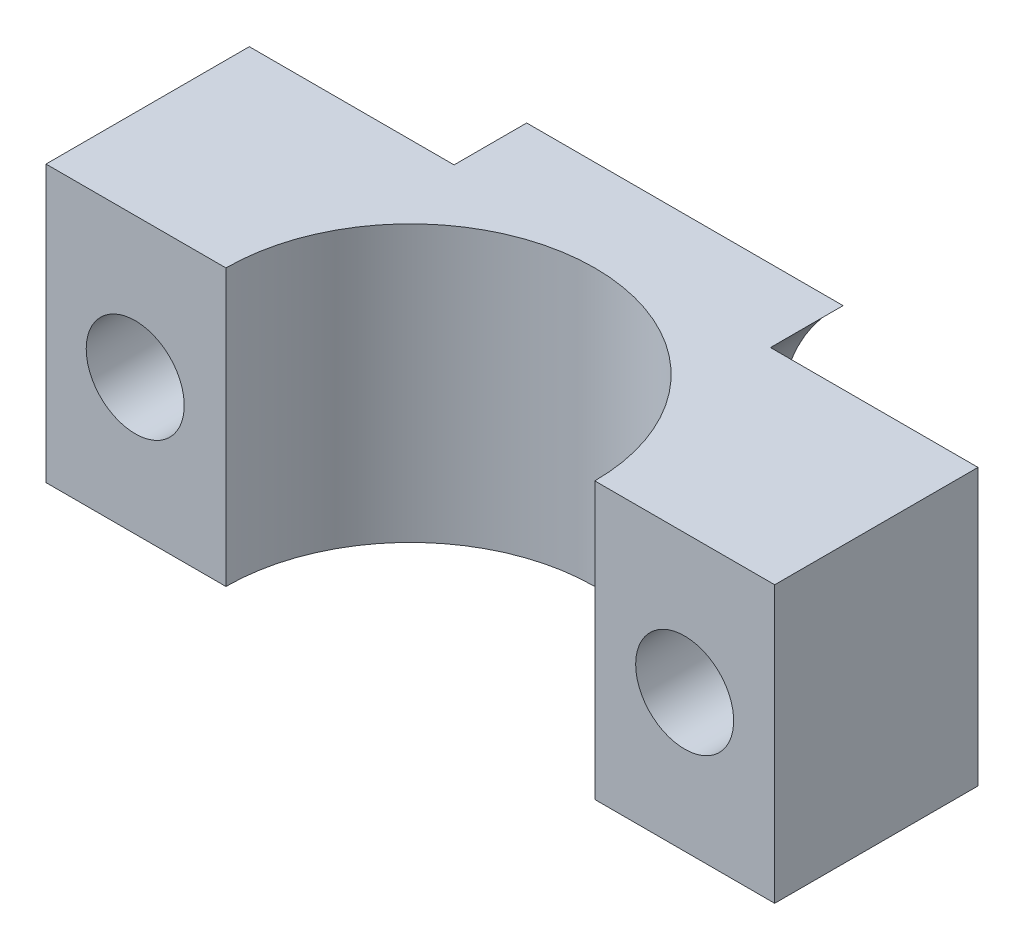
SolidWorks part; units mm, degrees
ref_plane "Front Plane" through (0, 0, 0) normal (0, 0, 1) x (1, 0, 0)
ref_plane "Top Plane" through (0, 0, 0) normal (0, 1, 0) x (1, 0, 0)
ref_plane "Right Plane" through (0, 0, 0) normal (1, 0, 0) x (0, 0, -1)
sketch "Sketch1" plane through (0, 0, 0) normal (0, 1, 0) x (1, 0, 0)
  line L0 (-25.09, 0) -> (25.09, 0)
  line L1 (-25.09, 0) -> (-25.09, 19)
  line L2 (25.09, 0) -> (25.09, 19)
  line L3 (-25.09, 19) -> (25.09, 19)
  circle A0 centre (0, 0) radius 12.7
  point P0 (0, 0)
  dimension "D3" = 25.4
  dimension "D1" = 50.18
  dimension "D2" = 19
extrude "Boss-Extrude2" add sketch "Sketch1" along normal mid plane 19 contours A0 L0 L2 L3 L1
sketch "Sketch3" plane through (0, 0, 0) normal (0, 0, 1) x (1, 0, 0)
  line L0 (-18.895, 9.5) -> (-18.895, -9.5) construction
  line L1 (18.895, 9.5) -> (18.895, -9.5) construction
  line L4 (-25.09, -9.5) -> (-12.7, -9.5)
  line L5 (-12.7, -9.5) -> (-12.7, 9.5)
  line L6 (-12.7, 9.5) -> (-25.09, 9.5)
  line L7 (-25.09, 9.5) -> (-25.09, -9.5)
  line L8 (-25.09, -9.5) -> (-12.7, -9.5)
  line L9 (-12.7, -9.5) -> (-12.7, 9.5)
  line L10 (-12.7, 9.5) -> (-25.09, 9.5)
  line L11 (-25.09, 9.5) -> (-25.09, -9.5)
  line L12 (12.7, -9.5) -> (25.09, -9.5)
  line L13 (25.09, -9.5) -> (25.09, 9.5)
  line L14 (25.09, 9.5) -> (12.7, 9.5)
  line L15 (12.7, 9.5) -> (12.7, -9.5)
  line L16 (12.7, -9.5) -> (25.09, -9.5)
  line L17 (25.09, -9.5) -> (25.09, 9.5)
  line L18 (25.09, 9.5) -> (12.7, 9.5)
  line L19 (12.7, 9.5) -> (12.7, -9.5)
  point P12 (18.895, 0)
  point P13 (-18.895, 0)
  dimension "D1" = 0
  dimension "D2" = 0
sketch "Sketch6" plane through (0, 0, -19) normal (0, 0, -1) x (-1, 0, 0)
  line L0 (12.7, -9.5) -> (12.7, 9.5) construction
  point P0 (-18.895, 0)
  point P1 (12.7, 0)
hole_wizard "CBORE for M12 Hex Head Bolt2" positions "3DSketch5" profile "Sketch13" counterbore size "M12" standard "ANSI Metric" end condition up to next
sketch3d "3DSketch5"
  point P0 (18.8898, -0.0281, -19)
  point P2 (-18.946, -0.1403, -19)
sketch "Sketch13" plane through (18.8898, -0.0281, -19) normal (1, 0, 0) x (0, 1, 0)
  line L0 (0, 0) -> (0, 19)
  line L1 (0, 19) -> (3.375, 19)
  line L3 (3.375, 19) -> (3.375, 5)
  line L4 (3.375, 5) -> (12.5, 5)
  line L5 (12.5, 5) -> (12.5, 0)
  line L7 (12.5, 0) -> (0, 0)
  line L11 (0, -6.35) -> (0, 107.95) construction
  dimension "Thru Hole Dia." = 6.75
  dimension "Thru Hole Depth" = 19
  dimension "C'Bore Dia." = 25
  dimension "C'Bore Depth" = 5
